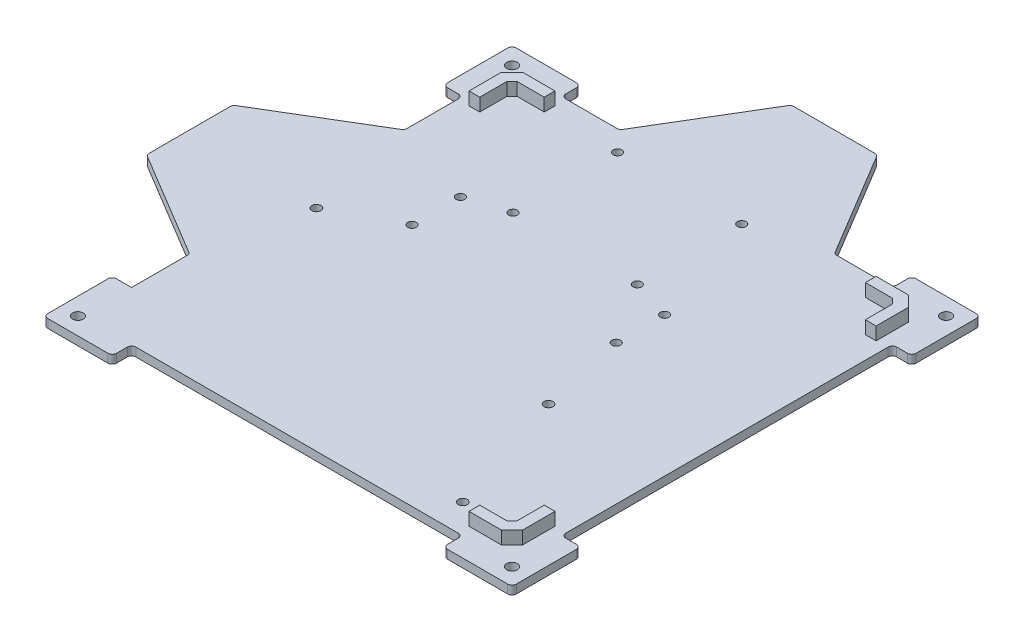
SolidWorks part; units mm, degrees
ref_plane "Plan de face" through (0, 0, 0) normal (0, 0, 1) x (1, 0, 0)
ref_plane "Plan de dessus" through (0, 0, 0) normal (0, 1, 0) x (1, 0, 0)
ref_plane "Plan de droite" through (0, 0, 0) normal (1, 0, 0) x (0, 0, -1)
sketch "Esquisse1" plane through (0, 0, 0) normal (0, 1, 0) x (1, 0, 0)
  line L20 (32, 234.4934) -> (32, -21.6261) construction
  line L21 (0, 0) -> (218, 0) construction
  line L22 (0, 0) -> (0, 218) construction
  line L23 (0, 218) -> (218, 218) construction
  line L24 (218, 0) -> (218, 218) construction
  line L25 (9, 209) -> (209, 209) construction
  line L26 (9, 209) -> (9, 9) construction
  line L27 (9, 9) -> (209, 9) construction
  line L28 (209, 209) -> (209, 9) construction
  line L29 (186, 234.4934) -> (186, -24.8818) construction
  line L30 (-33.4451, 186) -> (261.3817, 186) construction
  line L31 (-37.0626, 32) -> (249.4439, 32) construction
  line L32 (0, 218) -> (0, 186)
  line L33 (0, 186) -> (9, 186)
  line L34 (9, 186) -> (9, 159)
  line L35 (9, 32) -> (0, 32)
  line L36 (0, 32) -> (0, 0)
  line L37 (0, 0) -> (32, 0)
  line L38 (32, 0) -> (32, 9)
  line L39 (32, 9) -> (186, 9)
  line L40 (186, 9) -> (186, 0)
  line L41 (186, 0) -> (218, 0)
  line L42 (218, 0) -> (218, 32)
  line L43 (218, 32) -> (209, 32)
  line L44 (209, 32) -> (209, 186)
  line L45 (209, 186) -> (218, 186)
  line L46 (218, 186) -> (218, 218)
  line L47 (218, 218) -> (186, 218)
  line L48 (186, 218) -> (186, 209)
  line L49 (59, 209) -> (32, 209)
  line L50 (32, 209) -> (32, 218)
  line L51 (32, 218) -> (0, 218)
  line L52 (9, 59) -> (-41, 89)
  line L53 (-41, 89) -> (-41, 129)
  line L54 (-41, 129) -> (9, 159)
  line L55 (9, 59) -> (9, 32)
  line L56 (59, 209) -> (89, 259)
  line L57 (89, 259) -> (129, 259)
  line L58 (129, 259) -> (159, 209)
  line L59 (186, 209) -> (159, 209)
  circle A0 centre (8, 210) radius 2.5
  circle A1 centre (210, 210) radius 2.5
  circle A2 centre (210, 8) radius 2.5
  circle A3 centre (8, 8) radius 2.5
  point P35 (109, 109)
  point P38 (-41, 109)
  point P45 (109, 109)
  point P54 (109, 109)
  dimension "D11" = 5
  dimension "D1" = 218
  dimension "D2" = 218
  dimension "D3" = 9
  dimension "D4" = 9
  dimension "D5" = 9
  dimension "D6" = 9
  dimension "D7" = 32
  dimension "D8" = 32
  dimension "D9" = 32
  dimension "D10" = 32
  dimension "D12" = 8
  dimension "D13" = 8
  dimension "D15" = 40
  dimension "D16" = 50
  dimension "D17" = 30
  dimension "D18" = 30
  dimension "D19" = 109
  dimension "D20" = 2
  dimension "D14" = 4
extrude "Boss.-Extru.1" add sketch "Esquisse1" along normal blind 4
sketch "Esquisse2" plane through (0, 4, 0) normal (0, 1, 0) x (1, 0, 0)
  line L0 (32, 9) -> (186, 9) construction
  line L1 (204, 14) -> (14, 14) construction
  line L2 (204, 14) -> (204, 204) construction
  line L3 (204, 204) -> (14, 204) construction
  line L4 (14, 14) -> (14, 204) construction
  line L5 (209, 32) -> (209, 186) construction
  line L6 (59, 209) -> (32, 209) construction
  line L7 (9, 186) -> (9, 159) construction
  line L8 (204, 109) -> (14, 109) construction
  line L9 (204, 122.5) -> (14, 122.5) construction
  line L10 (144, 145) -> (49, 145) construction
  line L11 (96.5, 145) -> (96.5, 204) construction
  circle A3 centre (172.5, 22.6) radius 2.1
  circle A4 centre (153, 82) radius 2.1
  circle A5 centre (20, 107) radius 2.1
  circle A6 centre (49, 122.5) radius 2
  circle A7 centre (144, 122.5) radius 2
  circle A8 centre (144, 145) radius 2
  circle A9 centre (49, 145) radius 2
  circle A10 centre (67.6, 199.5) radius 2
  circle A11 centre (67.6, 150.9) radius 2
  circle A12 centre (125.4, 150.9) radius 2
  circle A13 centre (125.4, 199.5) radius 2
  point P12 (204, 122.5)
  point P37 (67.6, 199.5)
  point P38 (0, 0)
  dimension "D5" = 108.5
  dimension "D6" = 35
  dimension "D7" = 95
  dimension "D8" = 4
  dimension "D9" = 4
  dimension "D10" = 22.5
  dimension "D12" = 4
  dimension "D13" = 4
  dimension "D14" = 4
  dimension "D15" = 4
  dimension "D1" = 5
  dimension "D2" = 5
  dimension "D3" = 5
  dimension "D4" = 5
  dimension "D11" = 22.5
  dimension "D16" = 4.5
  dimension "D17" = 48.6
  dimension "D18" = 28.9
extrude "Enlèv. mat.-Extru.1" cut sketch "Esquisse2" against normal blind 4
sketch "Esquisse4" plane through (0, 4, 0) normal (0, 1, 0) x (1, 0, 0)
  line L0 (198.7, 14.3) -> (183.7, 14.3)
  line L1 (183.7, 14.3) -> (183.7, 19.3)
  line L4 (198.7, 34.3) -> (203.7, 34.3)
  line L5 (203.7, 34.3) -> (203.7, 19.3)
  line L6 (32, 9) -> (186, 9) construction
  line L7 (209, 32) -> (209, 186) construction
  line L8 (203.7, 19.3) -> (198.7, 14.3)
  line L9 (198.7, 21.6468) -> (196.3532, 19.3)
  line L10 (198.7, 34.3) -> (198.7, 21.6468)
  line L11 (196.3532, 19.3) -> (183.7, 19.3)
  line L20 (19.3, 203.7) -> (34.3, 203.7)
  line L21 (34.3, 203.7) -> (34.3, 198.7)
  line L22 (19.3, 183.7) -> (14.3, 183.7)
  line L23 (14.3, 183.7) -> (14.3, 198.7)
  line L24 (14.3, 198.7) -> (19.3, 203.7)
  line L25 (19.3, 196.3532) -> (21.6468, 198.7)
  line L26 (19.3, 183.7) -> (19.3, 196.3532)
  line L27 (21.6468, 198.7) -> (34.3, 198.7)
  line L28 (203.7, 198.7) -> (203.7, 183.7)
  line L29 (203.7, 183.7) -> (198.7, 183.7)
  line L30 (183.7, 198.7) -> (183.7, 203.7)
  line L31 (183.7, 203.7) -> (198.7, 203.7)
  line L32 (198.7, 203.7) -> (203.7, 198.7)
  line L33 (196.3532, 198.7) -> (198.7, 196.3532)
  line L34 (183.7, 198.7) -> (196.3532, 198.7)
  line L35 (198.7, 196.3532) -> (198.7, 183.7)
  line L36 (34.3, 19.3) -> (21.6468, 19.3) [skipped]
  line L37 (34.3, 14.3) -> (19.3, 14.3) [skipped]
  line L38 (34.3, 19.3) -> (34.3, 14.3) [skipped]
  line L39 (19.3, 14.3) -> (14.3, 19.3) [skipped]
  line L40 (21.6468, 19.3) -> (19.3, 21.6468) [skipped]
  line L41 (19.3, 21.6468) -> (19.3, 34.3) [skipped]
  line L42 (14.3, 19.3) -> (14.3, 34.3) [skipped]
  line L43 (14.3, 34.3) -> (19.3, 34.3) [skipped]
  point P4 (109, 109)
  point P40 (109, 109)
  dimension "D1" = 5.3
  dimension "D2" = 5.3
  dimension "D3" = 5
  dimension "D4" = 5
  dimension "D5" = 20
  dimension "D6" = 20
  dimension "D7" = 4
extrude "Boss.-Extru.2" add sketch "Esquisse4" along normal blind 6
fillet "Congé1" radius 2 27 edges at (32, 2, -209) (9, 2, -186) (0, 2, -186) (32, 2, -218) (0, 2, -218) (0, 2, -32) (32, 2, -9) (0, 2, 0) (32, 2, 0) (186, 2, -9) (186, 2, 0) (209, 2, -32) (218, 2, -32) (218, 2, 0) (209, 2, -186) (218, 2, -186) (218, 2, -218) (186, 2, -218) (9, 2, -59) (-41, 2, -89) (-41, 2, -129) (9, 2, -159) (59, 2, -209) (89, 2, -259) (129, 2, -259) (159, 2, -209) (186, 2, -209)
